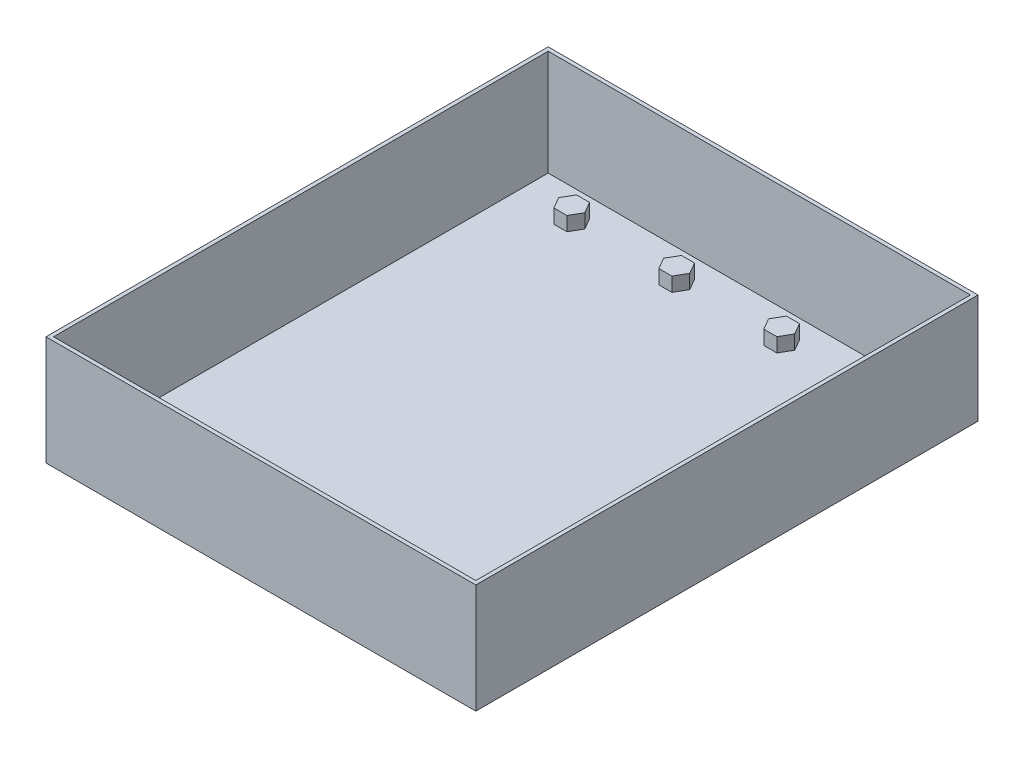
SolidWorks part; units mm, degrees
ref_plane "Front Plane" through (0, 0, 0) normal (0, 0, 1) x (1, 0, 0)
ref_plane "Top Plane" through (0, 0, 0) normal (0, 1, 0) x (1, 0, 0)
ref_plane "Right Plane" through (0, 0, 0) normal (1, 0, 0) x (0, 0, -1)
sketch "Sketch1" plane through (0, 0, 0) normal (0, 1, 0) x (1, 0, 0)
  line L1 (-90.4875, 105.7275) -> (90.4875, 105.7275)
  line L2 (-90.4875, 105.7275) -> (-90.4875, -105.7275)
  line L3 (-90.4875, -105.7275) -> (90.4875, -105.7275)
  line L4 (90.4875, 105.7275) -> (90.4875, -105.7275)
  line L5 (-90.4875, 105.7275) -> (90.4875, -105.7275) construction
  line L6 (-90.4875, -105.7275) -> (90.4875, 105.7275) construction
  point P0 (0, 0)
  dimension "D1" = 180.975
  dimension "D2" = 211.455
extrude "Boss-Extrude1" add sketch "Sketch1" along normal blind 46.0375
shell "Shell1" thickness 1.5875
sketch "Sketch3" plane through (0, 1.5875, 0) normal (0, 1, 0) x (1, 0, 0)
  line L0 (-27.5973, -91.44) -> (-24.8476, -96.2025)
  line L1 (-71.7933, -91.44) -> (-69.0436, -96.2025)
  line L2 (-69.0436, -96.2025) -> (-63.5444, -96.2025)
  line L3 (-63.5444, -96.2025) -> (-60.7947, -91.44)
  line L4 (-60.7947, -91.44) -> (-63.5444, -86.6775)
  line L5 (-63.5444, -86.6775) -> (-69.0436, -86.6775)
  line L6 (-69.0436, -86.6775) -> (-71.7933, -91.44)
  line L7 (-24.8476, -96.2025) -> (-19.3484, -96.2025)
  line L8 (-19.3484, -96.2025) -> (-16.5987, -91.44)
  line L9 (-16.5987, -91.44) -> (-19.3484, -86.6775)
  line L10 (-19.3484, -86.6775) -> (-24.8476, -86.6775)
  line L11 (-24.8476, -86.6775) -> (-27.5973, -91.44)
  line L12 (16.5987, -91.44) -> (19.3484, -96.2025)
  line L13 (19.3484, -96.2025) -> (24.8476, -96.2025)
  line L14 (24.8476, -96.2025) -> (27.5973, -91.44)
  line L15 (27.5973, -91.44) -> (24.8476, -86.6775)
  line L16 (24.8476, -86.6775) -> (19.3484, -86.6775)
  line L17 (19.3484, -86.6775) -> (16.5987, -91.44)
  line L18 (60.7947, -91.44) -> (63.5444, -96.2025)
  line L19 (63.5444, -96.2025) -> (69.0436, -96.2025)
  line L20 (69.0436, -96.2025) -> (71.7933, -91.44)
  line L21 (71.7933, -91.44) -> (69.0436, -86.6775)
  line L22 (69.0436, -86.6775) -> (63.5444, -86.6775)
  line L23 (63.5444, -86.6775) -> (60.7947, -91.44)
  line L24 (-27.5973, 91.44) -> (-24.8476, 86.6775)
  line L25 (-24.8476, 86.6775) -> (-19.3484, 86.6775)
  line L26 (-19.3484, 86.6775) -> (-16.5987, 91.44)
  line L27 (-16.5987, 91.44) -> (-19.3484, 96.2025)
  line L28 (-19.3484, 96.2025) -> (-24.8476, 96.2025)
  line L29 (-24.8476, 96.2025) -> (-27.5973, 91.44)
  line L30 (16.5987, 91.44) -> (19.3484, 86.6775)
  line L31 (19.3484, 86.6775) -> (24.8476, 86.6775)
  line L32 (24.8476, 86.6775) -> (27.5973, 91.44)
  line L33 (27.5973, 91.44) -> (24.8476, 96.2025)
  line L34 (24.8476, 96.2025) -> (19.3484, 96.2025)
  line L35 (19.3484, 96.2025) -> (16.5987, 91.44)
  line L36 (60.7947, 91.44) -> (63.5444, 86.6775)
  line L37 (63.5444, 86.6775) -> (69.0436, 86.6775)
  line L38 (69.0436, 86.6775) -> (71.7933, 91.44)
  line L39 (71.7933, 91.44) -> (69.0436, 96.2025)
  line L40 (69.0436, 96.2025) -> (63.5444, 96.2025)
  line L41 (63.5444, 96.2025) -> (60.7947, 91.44)
  line L42 (-71.7933, 91.44) -> (-69.0436, 86.6775)
  line L43 (-69.0436, 86.6775) -> (-63.5444, 86.6775)
  line L44 (-63.5444, 86.6775) -> (-60.7947, 91.44)
  line L45 (-60.7947, 91.44) -> (-63.5444, 96.2025)
  line L46 (-63.5444, 96.2025) -> (-69.0436, 96.2025)
  line L47 (-69.0436, 96.2025) -> (-71.7933, 91.44)
  line L48 (66.294, 91.44) -> (-66.294, -91.44) construction
  circle A0 centre (-66.294, -91.44) radius 4.7625 construction
  circle A1 centre (-22.098, -91.44) radius 4.7625 construction
  circle A2 centre (22.098, -91.44) radius 4.7625 construction
  circle A3 centre (66.294, -91.44) radius 4.7625 construction
  circle A4 centre (-22.098, 91.44) radius 4.7625 construction
  circle A5 centre (22.098, 91.44) radius 4.7625 construction
  circle A6 centre (66.294, 91.44) radius 4.7625 construction
  circle A7 centre (-66.294, 91.44) radius 4.7625 construction
  point P1 (0, 0)
  dimension "D1" = 9.525
  dimension "D4" = 44.196
  dimension "D5" = 182.88
  dimension "D2" = 4
  dimension "D3" = 2
extrude "Boss-Extrude2" add sketch "Sketch3" along normal blind 5.9531
